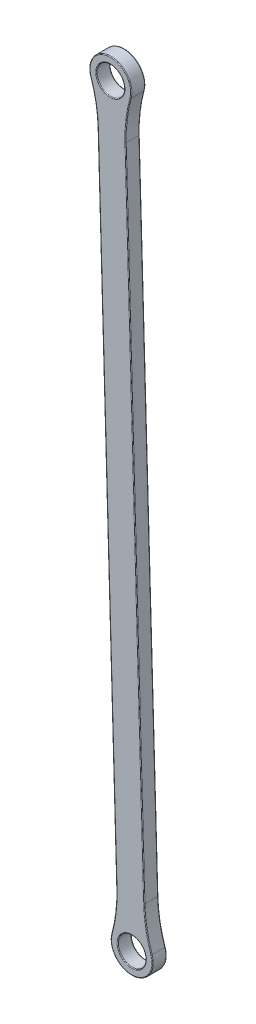
SolidWorks part; units mm, degrees
ref_plane "Front Plane" through (0, 0, 0) normal (0, 0, 1) x (1, 0, 0)
ref_plane "Top Plane" through (0, 0, 0) normal (0, 1, 0) x (1, 0, 0)
ref_plane "Right Plane" through (0, 0, 0) normal (1, 0, 0) x (0, 0, -1)
sketch "Sketch1" plane through (0, 0, 0) normal (0, 0, 1) x (1, 0, 0)
  line L0 (33.7427, 59.5858) -> (29.1483, 219.5198) construction
  line L1 (33.7427, 59.5858) -> (29.1483, 219.5198) construction
sketch "Sketch2" plane through (0, 0, 0) normal (0, 0, 1) x (1, 0, 0)
  line L0 (33.7427, 59.5858) -> (29.1483, 219.5198) construction
  line L1 (33.7427, 59.5858) -> (29.1483, 219.5198) construction
  line L2 (30.744, 59.4997) -> (26.1495, 219.4337)
  line L3 (36.7415, 59.672) -> (32.147, 219.606)
  circle A0 centre (29.1483, 219.5198) radius 4.5
  circle A1 centre (33.7427, 59.5858) radius 4.5
  arc A2 (30.744, 59.4997) -> (36.7415, 59.672) centre (33.7427, 59.5858) ccw
  arc A3 (32.147, 219.606) -> (26.1495, 219.4337) centre (29.1483, 219.5198) ccw
  arc A4 (26.1495, 219.4337) -> (32.147, 219.606) centre (29.1483, 219.5198) ccw
  arc A5 (30.744, 59.4997) -> (36.7415, 59.672) centre (33.7427, 59.5858) cw
  point P7 (31.4455, 139.5528)
  dimension "D1" = 9
  dimension "D3" = 9
  dimension "D2" = 6
extrude "Boss-Extrude3" add sketch "Sketch2" against normal blind 3 contours A3 L3 A0 L2 | A0 L0 A4 L2 | L0 A0 L3 A4 | A1 L0 A0 L2 | L0 A1 L3 A0 | A5 L0 A1 L2 | L0 A5 L3 A1 | A2 L2 A1 L3
fillet "Fillet5" radius 30 4 edges at (32.2434, 216.2533, -1.5) (26.2458, 216.081, -1.5) (30.6477, 62.8524, -1.5) (36.6452, 63.0247, -1.5)
fillet "Fillet6" radius 0.15 20 edges at (36.7427, 59.5858, -3) (36.7427, 59.5858, 0) (32.1483, 219.5198, -3) (32.1483, 219.5198, 0) (36.9073, 65.3181, -3) (36.9073, 65.3181, 0) (34.4443, 139.639, -3) (34.4443, 139.639, 0) (32.6367, 213.9787, -3) (32.6367, 213.9787, 0) (29.0191, 224.018, 0) (29.0191, 224.018, -3) (25.9837, 213.7876, -3) (25.9837, 213.7876, 0) (28.4467, 139.4667, 0) (28.4467, 139.4667, -3) (30.2543, 65.127, -3) (30.2543, 65.127, 0) (33.872, 55.0877, 0) (33.872, 55.0877, -3)
